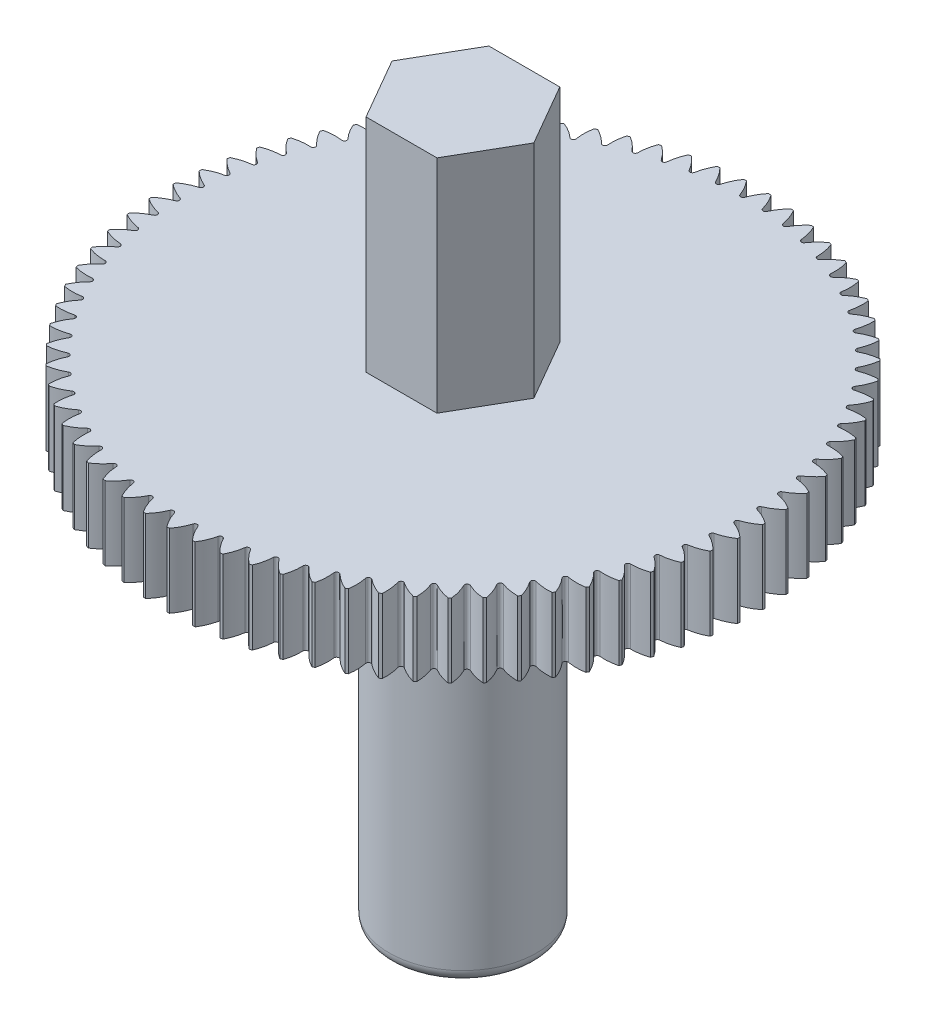
SolidWorks part; units mm, degrees
ref_plane "Front Plane" through (0, 0, 0) normal (0, 0, 1) x (1, 0, 0)
ref_plane "Top Plane" through (0, 0, 0) normal (0, 1, 0) x (1, 0, 0)
ref_plane "Right Plane" through (0, 0, 0) normal (1, 0, 0) x (0, 0, -1)
sketch "Sketch2" plane through (0, 0, 0) normal (0, 0, 1) x (1, 0, 0)
  line L0 (0, 0) -> (0, 29)
  line L1 (0, 0) -> (3, 0)
  line L2 (3, 0) -> (3, 17)
  line L3 (3, 17) -> (12, 17)
  line L4 (12, 17) -> (12, 20)
  line L5 (12, 20) -> (3, 20)
  line L6 (3, 20) -> (3, 29)
  line L7 (3, 29) -> (0, 29)
  dimension "D1" = 29
  dimension "D2" = 3
  dimension "D3" = 17
  dimension "D4" = 9
  dimension "D5" = 3
  dimension "D6" = 9
revolve "Revolve1" add sketch "Sketch2" angle 360 about L0
fillet "Fillet1" radius 0.5 1 edges at (0, 0, -3)
sketch "Sketch3" plane through (0, 29, 0) normal (0, 1, 0) x (1, 0, 0)
  line L1 (1.4434, 2.5) -> (-1.4434, 2.5)
  line L2 (-1.4434, 2.5) -> (-2.8868, 0)
  line L3 (-2.8868, 0) -> (-1.4434, -2.5)
  line L4 (-1.4434, -2.5) -> (1.4434, -2.5)
  line L5 (1.4434, -2.5) -> (2.8868, 0)
  line L6 (2.8868, 0) -> (1.4434, 2.5)
  circle A0 centre (0, 0) radius 2.5 construction
  circle A1 centre (0, 0) radius 3 construction
  circle A2 centre (0, 0) radius 3
  dimension "D1" = 5
extrude "Cut-Extrude1" cut sketch "Sketch3" against normal blind 9
sketch "Sketch4" plane through (0, 20, 0) normal (0, 1, 0) x (1, 0, 0)
  line L0 (0, 0) -> (0, 15.7858) construction
  arc A0 (-0.45, 11.9916) -> (-0.0942, 11.3714) centre (-1.979, 10.7023) cw
  circle A1 centre (0, 0) radius 12 construction
  arc A2 (0.45, 11.9916) -> (0.0942, 11.3714) centre (1.979, 10.7023) ccw
  arc A3 (0.45, 11.9916) -> (-0.45, 11.9916) centre (0, 0) ccw
  arc A4 (-0.0942, 11.3714) -> (0.0942, 11.3714) centre (0, 11.4049) ccw
  point P13 (0, 10.9916)
  dimension "D3" = 2
  dimension "D4" = 2
  dimension "D5" = 0.1
  dimension "D1" = 0.9
  dimension "D2" = 1
extrude "Cut-Extrude2" cut sketch "Sketch4" against normal up to next
pattern_circular "CirPattern1" count 75 over 360 about axis through (0, 0, 0) along (0, 1, 0) of "Cut-Extrude2"
